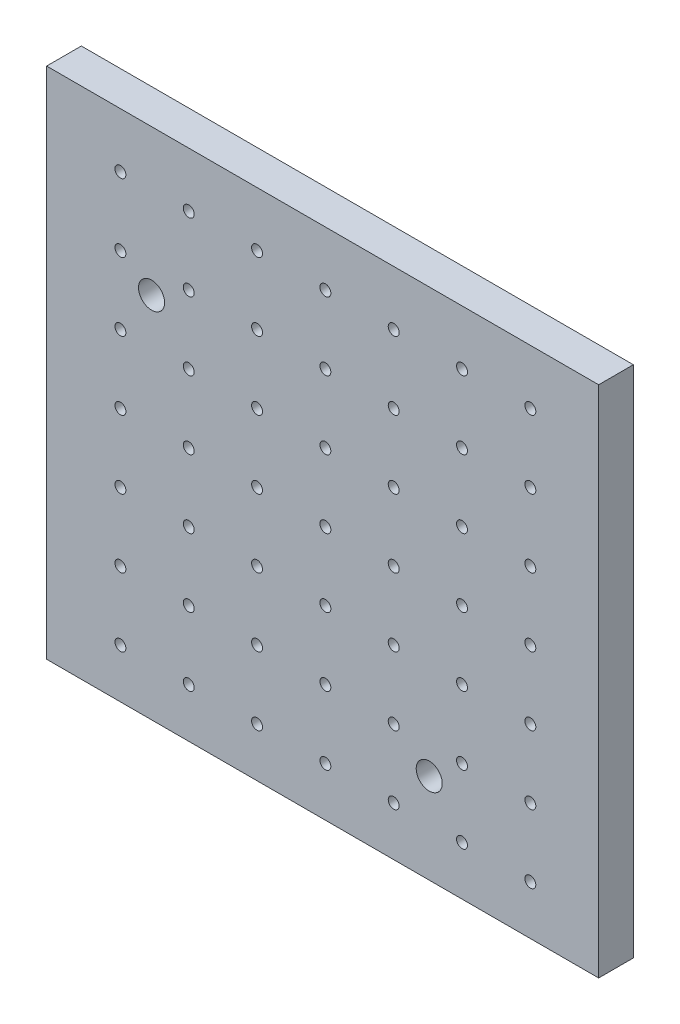
SolidWorks part; units mm, degrees
ref_plane "Alzado" through (0, 0, 0) normal (0, 0, 1) x (1, 0, 0)
ref_plane "Planta" through (0, 0, 0) normal (0, 1, 0) x (1, 0, 0)
ref_plane "Vista lateral" through (0, 0, 0) normal (1, 0, 0) x (0, 0, -1)
sketch "Croquis1" plane through (0, 0, 0) normal (0, 0, 1) x (1, 0, 0)
  line L1 (-101, 94) -> (101, 94)
  line L2 (-101, 94) -> (-101, -94)
  line L3 (-101, -94) -> (101, -94)
  line L4 (101, 94) -> (101, -94)
  line L5 (-101, 94) -> (101, -94) construction
  line L6 (-101, -94) -> (101, 94) construction
  point P0 (0, 0)
  dimension "D1" = 202
  dimension "D2" = 188
extrude "Saliente-Extruir1" add sketch "Croquis1" along normal blind 12.7
sketch "Croquis2" plane through (0, 0, 12.7) normal (0, 0, 1) x (1, 0, 0)
  line L0 (-101, 94) -> (-101, -94) construction
  line L1 (-101, -94) -> (101, -94) construction
  line L2 (101, -94) -> (101, 94) construction
  circle A0 centre (-74, -76) radius 2
  circle A1 centre (-49, -76) radius 2
  circle A2 centre (-24, -76) radius 2
  circle A3 centre (1, -76) radius 2
  circle A4 centre (26, -76) radius 2
  circle A5 centre (51, -76) radius 2
  circle A6 centre (76, -76) radius 2
  circle A7 centre (-49, -51) radius 2
  circle A8 centre (-24, -51) radius 2
  circle A9 centre (1, -51) radius 2
  circle A10 centre (26, -51) radius 2
  circle A11 centre (51, -51) radius 2
  circle A12 centre (76, -51) radius 2
  circle A13 centre (-49, -26) radius 2
  circle A14 centre (-24, -26) radius 2
  circle A15 centre (1, -26) radius 2
  circle A16 centre (26, -26) radius 2
  circle A17 centre (51, -26) radius 2
  circle A18 centre (76, -26) radius 2
  circle A19 centre (-49, -1) radius 2
  circle A20 centre (-24, -1) radius 2
  circle A21 centre (1, -1) radius 2
  circle A22 centre (26, -1) radius 2
  circle A23 centre (51, -1) radius 2
  circle A24 centre (76, -1) radius 2
  circle A25 centre (-49, 24) radius 2
  circle A26 centre (-24, 24) radius 2
  circle A27 centre (1, 24) radius 2
  circle A28 centre (26, 24) radius 2
  circle A29 centre (51, 24) radius 2
  circle A30 centre (76, 24) radius 2
  circle A31 centre (-49, 49) radius 2
  circle A32 centre (-24, 49) radius 2
  circle A33 centre (1, 49) radius 2
  circle A34 centre (26, 49) radius 2
  circle A35 centre (51, 49) radius 2
  circle A36 centre (76, 49) radius 2
  circle A37 centre (-49, 74) radius 2
  circle A38 centre (-24, 74) radius 2
  circle A39 centre (1, 74) radius 2
  circle A40 centre (26, 74) radius 2
  circle A41 centre (51, 74) radius 2
  circle A42 centre (76, 74) radius 2
  circle A43 centre (-74, -51) radius 2
  circle A44 centre (-74, -26) radius 2
  circle A45 centre (-74, -1) radius 2
  circle A46 centre (-74, 24) radius 2
  circle A47 centre (-74, 49) radius 2
  circle A48 centre (-74, 74) radius 2
  circle A49 centre (39, -61) radius 4.765
  circle A50 centre (-62.6, 40.6) radius 4.765
  dimension "D3" = 4
  dimension "D8" = 9.53
  dimension "D1" = 27
  dimension "D2" = 18
  dimension "D6" = 33
  dimension "D7" = 62
  dimension "D9" = 163.6
  dimension "D10" = 134.6
  dimension "D4" = 7
  dimension "D5" = 7
extrude "Cortar-Extruir1" cut sketch "Croquis2" against normal blind 12.7
